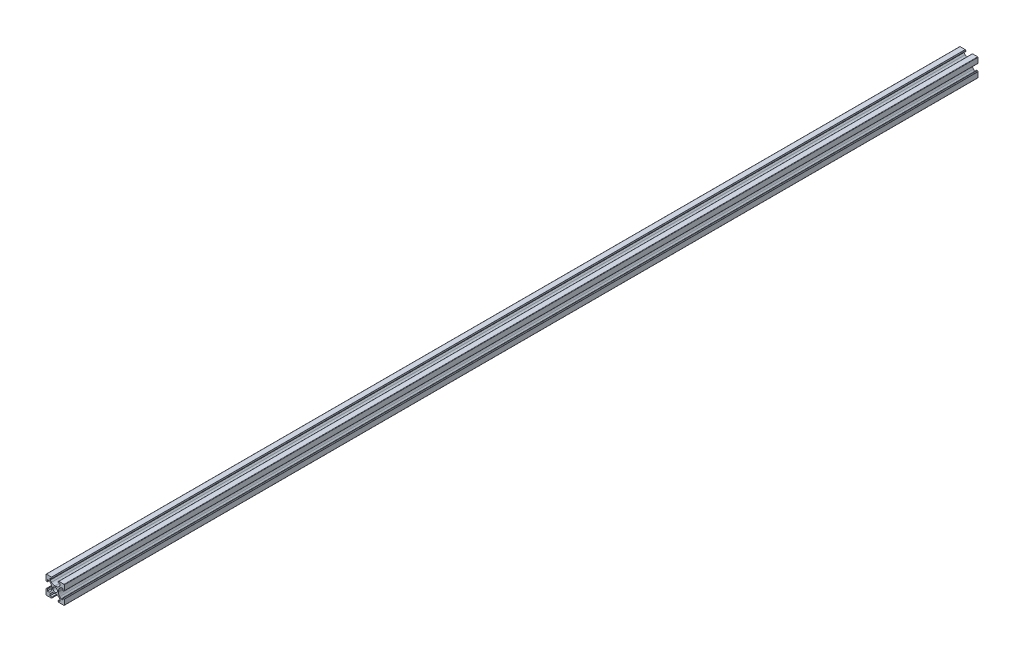
SolidWorks part; units mm, degrees
material "6063-T83"
ref_plane "Plano frontal" through (0, 0, 0) normal (0, 0, 1) x (1, 0, 0)
ref_plane "Plano superior" through (0, 0, 0) normal (0, 1, 0) x (1, 0, 0)
ref_plane "Plano direito" through (0, 0, 0) normal (1, 0, 0) x (0, 0, -1)
sketch "Esboço1" plane through (0, 0, 0) normal (0, 0, 1) x (1, 0, 0)
  line L0 (-9.0343, 3.1) -> (-8.9, 3.1)
  line L3 (-10, 10) -> (-4.0657, 10)
  line L5 (-10, -10) -> (10, 10) construction
  line L6 (-10, 10) -> (10, -10) construction
  line L7 (-8.5, 3.5) -> (-8.5, 5.5)
  line L8 (-10, 0) -> (10, 0) construction
  line L9 (0, 10) -> (0, -10) construction
  line L12 (-8.5, 5.5) -> (-6.5607, 5.5)
  line L15 (-6.5607, 5.5) -> (-5.0645, 4.0038)
  line L16 (-3.6, 0.4683) -> (-3.6, 0)
  line L17 (-0.4683, 3.6) -> (0, 3.6)
  line L18 (-5.5, 6.5607) -> (-4.0038, 5.0645)
  line L21 (-5.5, 8.5) -> (-5.5, 6.5607)
  line L24 (-3.5, 8.5) -> (-5.5, 8.5)
  line L25 (-3.1, 9.0343) -> (-3.1, 8.9)
  line L44 (-10, 4.0657) -> (-10, 10)
  line L45 (-9.8828, 3.7828) -> (-9.3172, 3.2172)
  line L46 (-3.7828, 9.8828) -> (-3.2172, 9.3172)
  line L47 (-3.6, 0) -> (-2.5, 0)
  line L48 (0, 3.6) -> (0, 2.5)
  arc A0 (-3.5, 8.5) -> (-3.1, 8.9) centre (-3.5, 8.9) ccw
  arc A1 (-3.7828, 9.8828) -> (-4.0657, 10) centre (-4.0657, 9.6) ccw
  arc A2 (-10, 4.0657) -> (-9.8828, 3.7828) centre (-9.6, 4.0657) ccw
  arc A3 (-8.5, 3.5) -> (-8.9, 3.1) centre (-8.9, 3.5) cw
  arc A4 (-3.2172, 9.3172) -> (-3.1, 9.0343) centre (-3.5, 9.0343) cw
  arc A5 (-9.3172, 3.2172) -> (-9.0343, 3.1) centre (-9.0343, 3.5) ccw
  arc A6 (-3.6, 0.4683) -> (-5.0645, 4.0038) centre (-8.6, 0.4683) ccw
  arc A7 (-4.0038, 5.0645) -> (-0.4683, 3.6) centre (-0.4683, 8.6) ccw
  circle A8 centre (0, 0) radius 2.5
  point P6 (-10, 3.1)
  point P28 (-3.1, 8.5)
  point P31 (-3.1, 10)
  point P33 (-3.9, 10)
  point P36 (-10, 3.9)
  point P39 (-8.5, 3.1)
  point P42 (-3.1, 9.2)
  point P45 (-9.2, 3.1)
  point P48 (-3.6, 2.5393)
  point P51 (-2.5393, 3.6)
  dimension "D5" = 10
  dimension "D9" = 0.4
  dimension "D10" = 0.4
  dimension "D11" = 5
  dimension "D12" = 5
  dimension "D13" = 5
  dimension "D1" = 6.9
  dimension "D2" = 1.5
  dimension "D3" = 3.6
  dimension "D4" = 1.5
  dimension "D6" = 2.4
  dimension "D7" = 3.6
  dimension "D8" = 45
extrude "Ressalto-extrusão1" add sketch "Esboço1" along normal blind 1000
sketch "Esboço3" plane through (0, 0, 0) normal (1, 0, 0) x (0, 0, -1)
  line L0 (0, 0) -> (-1000, 0) construction
  dimension "D1" = 1000
pattern_circular "PadrãoCircular1" count 4 every 90 about axis through (0, 0, 0) along (0, 0, 1) of "Ressalto-extrusão1"
fillet "Filete1" radius 0.4 4 edges at (-10, -10, 500) (-10, 10, 500) (10, -10, 500) (10, 10, 500)
